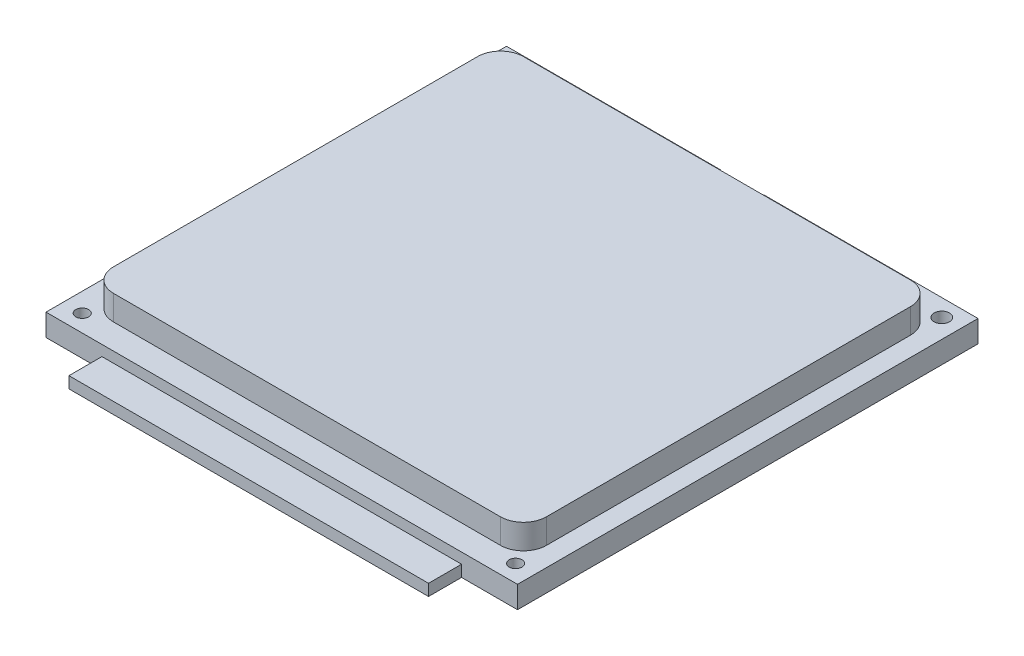
SolidWorks part; units mm, degrees
ref_plane "Front Plane" through (0, 0, 0) normal (0, 0, 1) x (1, 0, 0)
ref_plane "Top Plane" through (0, 0, 0) normal (0, 1, 0) x (1, 0, 0)
ref_plane "Right Plane" through (0, 0, 0) normal (1, 0, 0) x (0, 0, -1)
sketch "Sketch1" plane through (0, 0, 0) normal (0, 1, 0) x (1, 0, 0)
  line L1 (-32.639, 31.877) -> (32.639, 31.877)
  line L2 (-32.639, 31.877) -> (-32.639, -31.877)
  line L3 (-32.639, -31.877) -> (32.639, -31.877)
  line L4 (32.639, 31.877) -> (32.639, -31.877)
  line L5 (-32.639, 31.877) -> (32.639, -31.877) construction
  line L6 (-32.639, -31.877) -> (32.639, 31.877) construction
  point P0 (0, 0)
  dimension "D1" = 63.754
  dimension "D2" = 65.278
extrude "Boss-Extrude1" add sketch "Sketch1" along normal blind 3.048
sketch "Sketch2" plane through (0, 3.048, 0) normal (0, 1, 0) x (1, 0, 0)
  line L1 (-29.972, 28.3845) -> (29.972, 28.3845)
  line L2 (-29.972, 28.3845) -> (-29.972, -28.3845)
  line L3 (-29.972, -28.3845) -> (29.972, -28.3845)
  line L4 (29.972, 28.3845) -> (29.972, -28.3845)
  line L5 (-29.972, 28.3845) -> (29.972, -28.3845) construction
  line L6 (-29.972, -28.3845) -> (29.972, 28.3845) construction
  point P0 (0, 0)
  dimension "D1" = 59.944
  dimension "D2" = 56.769
extrude "Boss-Extrude2" add sketch "Sketch2" along normal blind 3.429
sketch "Sketch3" plane through (0, 3.048, 0) normal (0, 1, 0) x (1, 0, 0)
  line L0 (-30, 29.5) -> (30, -29.5) construction
  circle A0 centre (-30, 29.5) radius 1.0668
  circle A1 centre (30, 29.5) radius 1.0668
  circle A2 centre (30, -29.5) radius 0.889
  circle A3 centre (-30, -29.5) radius 0.889
  dimension "D1" = 2.1336
  dimension "D2" = 1.778
  dimension "D3" = 59
  dimension "D4" = 60
extrude "Cut-Extrude1" cut sketch "Sketch3" against normal through all
fillet "Fillet1" radius 3.175 4 edges at (-29.972, 4.7625, -28.3845) (29.972, 4.7625, -28.3845) (29.972, 4.7625, 28.3845) (-29.972, 4.7625, 28.3845)
sketch "Sketch4" plane through (0, 3.048, 0) normal (0, 1, 0) x (1, 0, 0)
  line L0 (32.639, 31.877) -> (-32.639, 31.877) construction
  line L1 (-2.9845, 28.3845) -> (2.9845, 28.3845)
  line L2 (-2.9845, 28.3845) -> (-2.9845, 31.877)
  line L3 (-2.9845, 31.877) -> (2.9845, 31.877)
  line L4 (2.9845, 28.3845) -> (2.9845, 31.877)
  line L5 (-2.9845, 28.3845) -> (2.9845, 31.877) construction
  line L6 (-2.9845, 31.877) -> (2.9845, 28.3845) construction
  line L7 (26.797, 28.3845) -> (-26.797, 28.3845) construction
  point P0 (0, 30.1307)
  dimension "D1" = 5.969
extrude "Cut-Extrude2" cut sketch "Sketch4" against normal through all
sketch "Sketch5" plane through (0, 0, 0) normal (0, -1, 0) x (1, 0, 0)
  line L0 (-32.639, 31.877) -> (32.639, 31.877) construction
  line L1 (-24.892, 36.449) -> (24.892, 36.449)
  line L2 (-24.892, 36.449) -> (-24.892, 31.877)
  line L3 (-24.892, 31.877) -> (24.892, 31.877)
  line L4 (24.892, 36.449) -> (24.892, 31.877)
  line L5 (-24.892, 36.449) -> (24.892, 31.877) construction
  line L6 (-24.892, 31.877) -> (24.892, 36.449) construction
  point P0 (0, 34.163)
  dimension "D1" = 49.784
  dimension "D2" = 4.572
extrude "Boss-Extrude3" add sketch "Sketch5" against normal blind 1.5875
